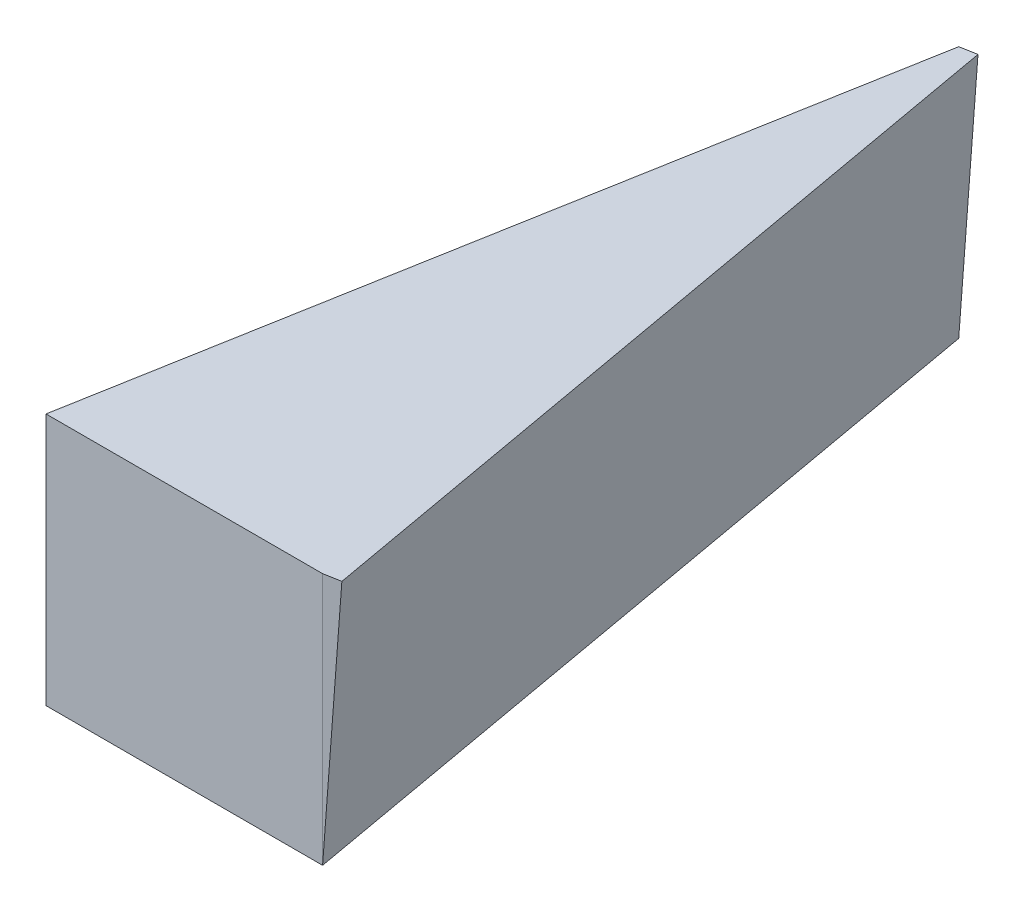
SolidWorks part; units mm, degrees
material "AISI 4340 Steel, annealed"
ref_plane "Front Plane" through (0, 0, 0) normal (0, 0, 1) x (1, 0, 0)
ref_plane "Top Plane" through (0, 0, 0) normal (0, 1, 0) x (1, 0, 0)
ref_plane "Right Plane" through (0, 0, 0) normal (1, 0, 0) x (0, 0, -1)
sketch "Sketch1" plane through (0, 0, 0) normal (0, 1, 0) x (1, 0, 0)
  line L0 (0, 0) -> (-71.265, -399.0667)
  line L1 (-71.265, -399.0667) -> (71.265, -399.0667)
  line L2 (71.265, -399.0667) -> (0, 0)
  point P4 (0, -399.0667)
  dimension "D1" = 405.38
  dimension "D2" = 142.53
extrude "Main block extrude" add sketch "Sketch1" along normal mid plane 130.18
shell "Shell1" thickness 5
ref_plane "Plane1" through (71.265, 0, 399.0667) normal (0.1758, 0, 0.9844) x (0, -1, 0)
sketch "Sketch2" plane through (71.265, 0, 399.0667) normal (0.1758, 0, 0.9844) x (0, -1, 0)
  line L0 (-65.09, 0) -> (65.09, 0) construction
  line L1 (-65.09, 0) -> (65.09, 0)
  line L2 (-65.09, 0) -> (-65.09, 8.5604)
  line L3 (-65.09, 8.5604) -> (65.09, 0)
  dimension "D1" = 3.762
extrude "Slant" add sketch "Sketch2" against normal up to vertex (405.38 mm away)
